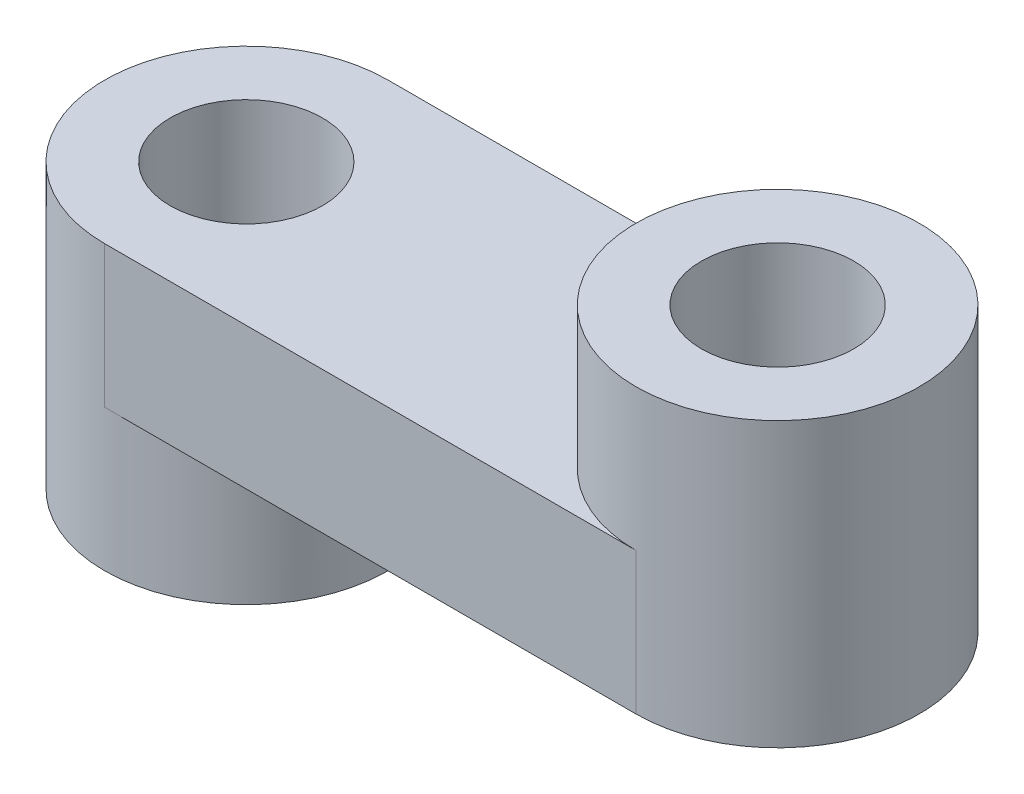
SolidWorks part; units mm, degrees
ref_plane "Front Plane" through (0, 0, 0) normal (0, 0, 1) x (1, 0, 0)
ref_plane "Top Plane" through (0, 0, 0) normal (0, 1, 0) x (1, 0, 0)
ref_plane "Right Plane" through (0, 0, 0) normal (1, 0, 0) x (0, 0, -1)
sketch "Sketch1" plane through (0, 0, 0) normal (0, 1, 0) x (1, 0, 0)
  line L0 (0, 2) -> (7.5, 2)
  line L1 (0, -2) -> (7.5, -2)
  arc A0 (0, 2) -> (0, -2) centre (0, 0) ccw
  arc A1 (7.5, -2) -> (7.5, 2) centre (7.5, 0) ccw
  circle A2 centre (0, 0) radius 1.075
  circle A3 centre (7.5, 0) radius 1.075
  point P9 (0, 0)
  dimension "D1" = 2.15
  dimension "D4" = 4
  dimension "D3" = 7.5
extrude "Boss-Extrude1" add sketch "Sketch1" along normal blind 6
sketch "Sketch2" plane through (0, 6, 0) normal (0, 1, 0) x (1, 0, 0)
  line L0 (0, 2) -> (7.5, 2)
  line L5 (7.5, -2) -> (0, -2)
  arc A0 (0, 2) -> (0, -2) centre (0, 0) ccw
  arc A1 (7.5, 2) -> (7.5, -2) centre (7.5, 0) ccw
  point P1 (0, 0)
  point P2 (7.5, 0)
  point P7 (0, 0)
  point P8 (0, 0)
  point P10 (0, 0)
  point P11 (0, 0)
  point P12 (0, 0)
  point P13 (0, 0)
extrude "Cut-Extrude1" cut sketch "Sketch2" against normal blind 2 contours A0 L5 A1 L0
sketch "Sketch3" plane through (0, 0, 0) normal (0, -1, 0) x (1, 0, 0)
  line L0 (7.5, 2) -> (0, 2)
  line L2 (0, -2) -> (7.5, -2)
  arc A0 (7.5, -2) -> (7.5, 2) centre (7.5, 0) ccw
  arc A1 (0, 2) -> (0, -2) centre (0, 0) cw
  point P1 (7.5, 0)
  point P5 (0, 0)
  point P6 (0, 0)
  point P7 (0, 0)
  point P8 (0, 0)
  point P10 (0, 0)
  point P11 (0, 0)
  point P17 (0, 0)
  point P19 (0, 0)
  point P21 (0, 0)
  point P25 (0, 0)
extrude "Cut-Extrude2" cut sketch "Sketch3" against normal blind 2
